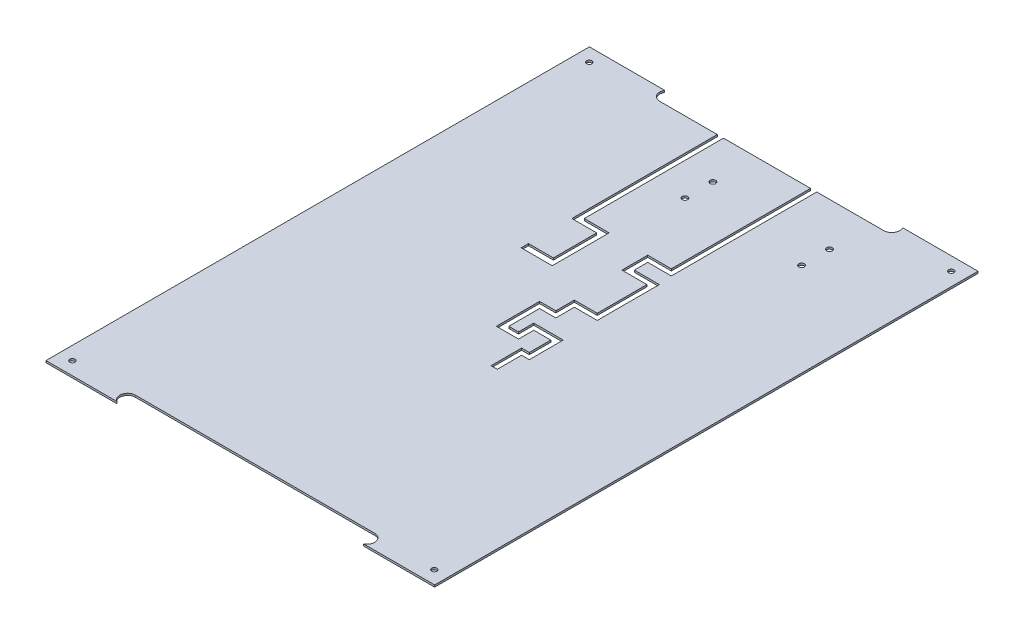
SolidWorks part; units mm, degrees
material "PC High Viscosity"
ref_plane "Front Plane" through (0, 0, 0) normal (0, 0, 1) x (1, 0, 0)
ref_plane "Top Plane" through (0, 0, 0) normal (0, 1, 0) x (1, 0, 0)
ref_plane "Right Plane" through (0, 0, 0) normal (1, 0, 0) x (0, 0, -1)
sketch "Sketch1" plane through (0, 0, 0) normal (0, 1, 0) x (1, 0, 0)
  line L0 (-97.79, -198.4375) -> (97.79, -198.4375) construction
  line L1 (-158.75, 239.7125) -> (158.75, 239.7125)
  line L2 (-158.75, 239.7125) -> (-158.75, -239.7125)
  line L3 (-158.75, -239.7125) -> (158.75, -239.7125)
  line L4 (158.75, 239.7125) -> (158.75, -239.7125)
  line L5 (-158.75, 239.7125) -> (158.75, -239.7125) construction
  line L6 (-158.75, -239.7125) -> (158.75, 239.7125) construction
  line L7 (-97.79, -192.0875) -> (97.79, -192.0875)
  line L8 (-97.79, -204.7875) -> (97.79, -204.7875)
  line L16 (-147.828, 228.7905) -> (147.828, 228.7905) construction
  line L17 (-126.365, 182.5625) -> (-126.365, 163.5125) construction
  line L18 (-104.14, 128.4605) -> (-104.14, 84.2645) construction
  line L19 (104.14, 128.4605) -> (104.14, 84.2645) construction
  line L20 (-104.14, 106.3625) -> (104.14, 106.3625) construction
  line L21 (0, 236.5375) -> (0, -198.4375) construction
  line L22 (-91.44, 236.5375) -> (91.44, 236.5375) construction
  line L23 (-91.44, 243.1447) -> (91.44, 243.1447)
  line L24 (-91.44, 229.9303) -> (91.44, 229.9303)
  arc A0 (-97.79, -192.0875) -> (-97.79, -204.7875) centre (-97.79, -198.4375) ccw
  arc A1 (97.79, -204.7875) -> (97.79, -192.0875) centre (97.79, -198.4375) ccw
  circle A4 centre (-147.828, 228.7905) radius 2.1527
  circle A5 centre (-147.828, -193.4845) radius 2.1527
  circle A6 centre (147.828, 228.7905) radius 2.1527
  circle A7 centre (147.828, -193.4845) radius 2.1527
  circle A8 centre (-104.14, 216.8525) radius 9.525
  circle A9 centre (104.14, 216.8525) radius 9.525
  circle A10 centre (104.14, 172.6565) radius 9.525
  circle A11 centre (-104.14, 172.6565) radius 9.525
  circle A12 centre (104.14, 128.4605) radius 9.525
  circle A13 centre (-104.14, 128.4605) radius 9.525
  circle A14 centre (104.14, 84.2645) radius 9.525 construction
  circle A15 centre (-104.14, 84.2645) radius 9.525 construction
  circle A16 centre (104.14, 40.0685) radius 9.525
  circle A17 centre (-104.14, 40.0685) radius 9.525
  circle A18 centre (104.14, -4.1275) radius 9.525
  circle A19 centre (-104.14, -4.1275) radius 9.525
  circle A20 centre (-104.14, 84.2645) radius 2.4892
  circle A21 centre (104.14, 84.2645) radius 2.4892
  circle A22 centre (-126.365, 182.5625) radius 2.1527
  circle A23 centre (-126.365, 163.5125) radius 2.1527
  circle A24 centre (-126.365, 49.2125) radius 2.1527
  circle A25 centre (-126.365, 30.1625) radius 2.1527
  circle A26 centre (126.365, 30.1625) radius 2.1527
  circle A27 centre (126.365, 49.2125) radius 2.1527
  circle A28 centre (126.365, 163.5125) radius 2.1527
  circle A29 centre (126.365, 182.5625) radius 2.1527
  arc A30 (-91.44, 243.1447) -> (-91.44, 229.9303) centre (-91.44, 236.5375) ccw
  arc A31 (91.44, 229.9303) -> (91.44, 243.1447) centre (91.44, 236.5375) ccw
  point P0 (0, 0)
  point P8 (0, -198.4375)
  point P13 (0, -198.4375)
  point P14 (0, -239.7125)
  point P15 (0, 0)
  point P37 (0, 228.7905)
  point P85 (0, 236.5375)
  dimension "D4" = 6.35
  dimension "D9" = 4.3053
  dimension "D11" = 19.05
  dimension "D17" = 4.9784
  dimension "D18" = 4.3053
  dimension "D6" = 67.31
  dimension "D1" = 317.5
  dimension "D2" = 479.425
  dimension "D3" = 60.96
  dimension "D5" = 41.275
  dimension "D7" = 10.922
  dimension "D8" = 10.922
  dimension "D10" = 46.228
  dimension "D12" = 54.61
  dimension "D13" = 22.86
  dimension "D14" = 54.61
  dimension "D16" = 44.196
  dimension "D19" = 22.225
  dimension "D20" = 19.05
  dimension "D21" = 9.906
  dimension "D22" = 67.31
  dimension "D15" = 6
extrude "Boss-Extrude1" add sketch "Sketch1" along normal blind 1.5875
sketch "Sketch2" plane through (0, 1.5875, 0) normal (0, 1, 0) x (1, 0, 0)
  line L0 (-97.79, 230.1875) -> (-93.2656, 230.1875) construction
  line L2 (-44.45, 230.1875) -> (-44.45, 111.1064)
  line L3 (-44.45, 111.1064) -> (-39.37, 111.1064)
  line L4 (-39.37, 230.1875) -> (-39.37, 116.1864)
  line L5 (158.75, 239.7125) -> (158.75, -239.7125) construction
  line L6 (-39.37, 116.1864) -> (-19.05, 116.1864)
  line L7 (-44.45, 116.1864) -> (-44.45, 111.1064)
  line L8 (-44.45, 111.1064) -> (-24.13, 111.1064)
  line L9 (-19.05, 116.1864) -> (-19.05, 111.1064)
  line L11 (-24.13, 111.1064) -> (-24.13, 80.774)
  line L13 (-19.05, 111.1064) -> (-19.05, 75.694)
  line L26 (-44.45, 230.1875) -> (-39.37, 230.1875)
  line L28 (31.75, 230.1875) -> (31.75, 116.1864)
  line L30 (36.83, 230.1875) -> (36.83, 116.1864)
  line L58 (14.2589, 49.3855) -> (14.2589, 39.3113)
  line L64 (26.67, -1.0687) -> (26.67, -26.035)
  line L65 (26.67, -26.035) -> (31.75, -26.035)
  line L66 (31.75, -6.1487) -> (31.75, -26.035)
  line L87 (31.75, 116.1864) -> (12.4783, 116.1864)
  line L88 (36.83, 116.1864) -> (36.83, 111.1064)
  line L89 (36.83, 111.1064) -> (17.5583, 111.1064)
  line L90 (12.4783, 116.1864) -> (12.4783, 111.1064)
  line L91 (26.67, -26.035) -> (31.75, -26.035)
  line L92 (26.67, -26.035) -> (26.67, -6.1487)
  line L94 (31.75, -26.035) -> (31.75, -6.1487)
  line L95 (26.67, -1.0687) -> (32.9448, -1.0687)
  line L96 (26.67, -1.0687) -> (26.67, -6.1487)
  line L97 (31.75, -6.1487) -> (38.0248, -6.1487)
  line L98 (38.0248, -1.0687) -> (38.0248, -6.1487)
  line L99 (32.9448, -6.1487) -> (38.0248, -6.1487)
  line L100 (32.9448, -1.0687) -> (32.9448, 16.5144)
  line L102 (38.0248, -6.1487) -> (38.0248, 21.5944)
  line L121 (19.3389, 34.2313) -> (14.2589, 34.2313)
  line L124 (14.2589, 39.3113) -> (14.2589, 54.4655)
  line L125 (14.2589, 54.4655) -> (19.3389, 54.4655)
  line L126 (19.3389, 39.3113) -> (19.3389, 49.3855)
  line L127 (14.2589, 54.4655) -> (32.9448, 54.4655)
  line L128 (14.2589, 54.4655) -> (14.2589, 49.3855)
  line L129 (19.3389, 49.3855) -> (38.0248, 49.3855)
  line L130 (38.0248, 54.4655) -> (38.0248, 49.3855)
  line L132 (32.9448, 54.4655) -> (32.9448, 94.3277)
  line L134 (38.0248, 54.4655) -> (38.0248, 94.3277)
  line L135 (32.9448, 95.043) -> (27.4669, 95.043)
  line L136 (38.0248, 95.043) -> (38.0248, 100.123)
  line L137 (38.0248, 100.123) -> (19.091, 100.123)
  line L140 (12.4783, 111.1064) -> (12.4783, 97.7255)
  line L142 (17.5583, 111.1064) -> (17.5583, 100.123)
  line L143 (19.091, 100.123) -> (17.5583, 100.123)
  line L144 (32.9448, 94.3277) -> (32.9448, 95.043)
  line L145 (31.75, 230.1875) -> (36.83, 230.1875)
  line L146 (38.0248, 94.3277) -> (38.0248, 95.043)
  line L147 (38.0248, 21.5944) -> (13.97, 21.5944)
  line L148 (38.0248, 21.5944) -> (38.0248, 16.5144)
  line L149 (32.9448, 16.5144) -> (19.05, 16.5144)
  line L150 (13.97, 21.5944) -> (13.97, 16.5144)
  line L151 (13.97, 21.5944) -> (19.05, 21.5944)
  line L152 (13.97, 21.5944) -> (13.97, 9.1263)
  line L153 (13.97, 4.0463) -> (19.05, 4.0463)
  line L154 (19.05, 16.5144) -> (19.05, 4.0463)
  line L155 (13.97, 9.1263) -> (6.0478, 9.1263)
  line L156 (19.05, 9.1263) -> (19.05, 4.0463)
  line L157 (19.05, 4.0463) -> (0.9678, 4.0463)
  line L158 (0.9678, 9.1263) -> (0.9678, 4.0463)
  line L159 (6.0478, 4.0463) -> (0.9678, 4.0463)
  line L160 (6.0478, 9.1263) -> (6.0478, 34.2313)
  line L161 (6.0478, 39.3113) -> (0.9678, 39.3113)
  line L162 (0.9678, 4.0463) -> (0.9678, 39.3113)
  line L163 (0.9678, 39.3113) -> (14.2589, 39.3113)
  line L164 (0.9678, 39.3113) -> (0.9678, 34.2313)
  line L165 (6.0478, 34.2313) -> (14.2589, 34.2313)
  line L167 (19.3389, 39.3113) -> (19.3389, 34.2313)
  line L168 (-39.37, 111.1064) -> (-24.13, 111.1064)
  line L169 (-24.13, 80.774) -> (-24.13, 75.694)
  line L172 (-24.13, 75.694) -> (-44.45, 75.694)
  line L173 (-44.45, 75.694) -> (-44.45, 69.6935)
  line L174 (-44.45, 69.6935) -> (-19.05, 69.6935)
  line L175 (-158.75, 239.7125) -> (-158.75, -239.7125) construction
  line L176 (-19.05, 75.694) -> (-19.05, 69.6935)
  line L177 (27.4669, 95.043) -> (12.4783, 95.043)
  line L178 (12.4783, 95.043) -> (12.4783, 97.7255)
  point P20 (12.4783, 104.416)
  dimension "D3" = 114.3
  dimension "D4" = 5.08
  dimension "D5" = 5.08
  dimension "D6" = 5.08
  dimension "D7" = 39.8623
  dimension "D8" = 25.4
  dimension "D9" = 127
  dimension "D10" = 5.08
  dimension "D11" = 5.08
  dimension "D12" = 190.5
  dimension "D13" = 5.08
  dimension "D14" = 5.08
  dimension "D15" = 5.08
  dimension "D16" = 5.08
  dimension "D17" = 5.08
  dimension "D18" = 5.08
  dimension "D19" = 5.08
  dimension "D20" = 5.08
  dimension "D21" = 5.08
  dimension "D22" = 5.08
  dimension "D23" = 5.08
  dimension "D24" = 5.08
  dimension "D25" = 5.08
extrude "Cut-Extrude1" cut sketch "Sketch2" against normal blind 2.54
sketch "Sketch4" plane through (0, 0, 0) normal (0, -1, 0) x (1, 0, 0)
  line L1 (-97.79, -230.1875) -> (-93.2656, -230.1875) construction
  line L2 (-39.37, -230.1875) -> (31.75, -230.1875) construction
  line L3 (-158.75, -239.7125) -> (-158.75, 239.7125) construction
  point P1 (-12.7, -194.6275)
  point P3 (82.55, -194.6275)
  point P6 (82.55, -171.7675)
  point P7 (-12.7, -171.7675)
  dimension "D1" = 22.86
  dimension "D2" = 22.86
  dimension "D3" = 95.25
  dimension "D4" = 146.05
  dimension "D5" = 35.56
  dimension "D6" = 35.56
hole_wizard "13/64 (0.18) Diameter Hole1" positions "Sketch5" profile "Sketch6" hole size "13/64" standard "ANSI Inch" end condition through all
sketch "Sketch5" plane through (0, 0, 0) normal (0, -1, 0) x (-1, 0, 0)
  point P0 (-82.55, 194.6275)
  point P9 (12.7, 194.6275)
  point P12 (-82.55, 171.7675)
  point P15 (12.7, 171.7675)
  point P18 (12.7, 194.6275)
  point P20 (-82.55, 194.6275)
sketch "Sketch6" plane through (82.55, 0, -194.6275) normal (1, 0, 0) x (0, 0, -1)
  line L0 (0, 0) -> (0, 1.5875)
  line L1 (0, 1.5875) -> (2.286, 1.5875)
  line L2 (2.286, 1.5875) -> (2.286, 0)
  line L5 (2.286, 0) -> (0, 0)
  line L11 (0, -6.35) -> (0, 107.95) construction
  dimension "Thru Hole Dia." = 4.572
  dimension "Thru Hole Depth" = 1.5875
sketch "Sketch7" plane through (0, 1.5875, 0) normal (0, 1, 0) x (1, 0, 0)
  line L0 (-158.75, 239.7125) -> (-158.75, -239.7125) construction
  line L1 (-158.75, -204.1525) -> (158.75, -204.1525)
  line L2 (-158.75, -204.1525) -> (-158.75, -239.7125)
  line L3 (-158.75, -239.7125) -> (158.75, -239.7125)
  line L4 (158.75, -204.1525) -> (158.75, -239.7125)
  line L5 (158.75, 239.7125) -> (158.75, -239.7125) construction
  dimension "D1" = 35.56
extrude "Cut-Extrude2" cut sketch "Sketch7" against normal through all
